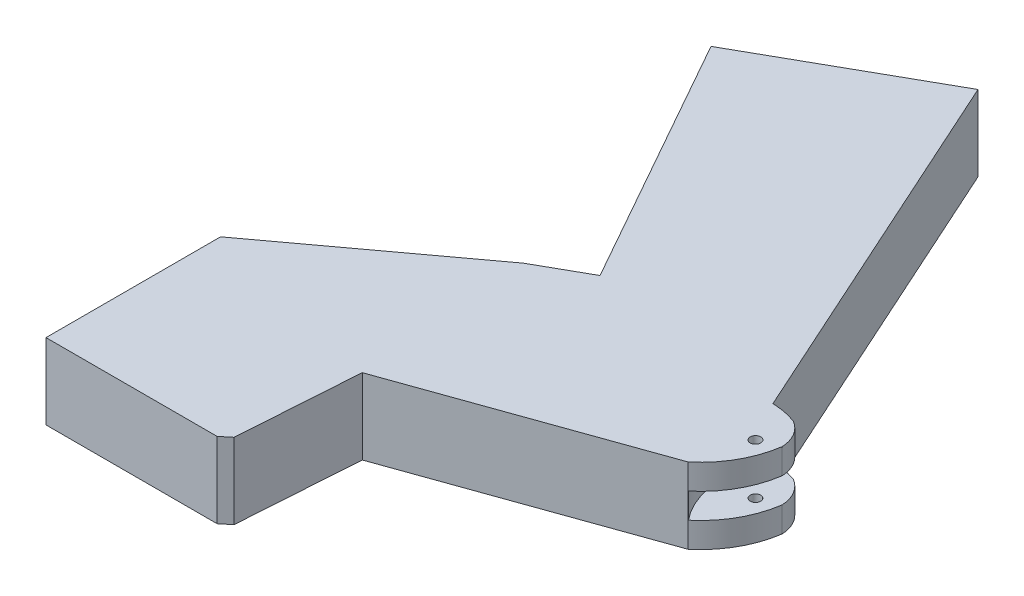
SolidWorks part; units mm, degrees
ref_plane "Front Plane" through (0, 0, 0) normal (0, 0, 1) x (1, 0, 0)
ref_plane "Top Plane" through (0, 0, 0) normal (0, 1, 0) x (1, 0, 0)
ref_plane "Right Plane" through (0, 0, 0) normal (1, 0, 0) x (0, 0, -1)
sketch "Sketch1" plane through (0, 0, 0) normal (0, 1, 0) x (1, 0, 0)
  line L0 (-30.4171, -25.1913) -> (-60.8342, -25.1913)
  line L1 (-8.2502, 1.4059) -> (-24.0712, 28.8087)
  line L2 (0, 0) -> (24.0712, 41.6926)
  line L4 (-24.0712, 28.8087) -> (-55.3265, 11.213)
  line L5 (-55.3265, 11.213) -> (-42.4527, -11.6547)
  line L6 (-42.4527, -11.6547) -> (-60.8342, -11.6547)
  line L7 (-60.8342, -11.6547) -> (-60.8342, -25.1913)
  line L9 (-9.9889, -8.2728) -> (-30.4171, -25.1913)
  arc A2 (-8.2502, 1.4059) -> (-9.9889, -8.2728) centre (-14.8493, -2.4041) cw
  point P3 (0, -25.1913)
  dimension "D2" = 7.62
  dimension "D1" = 60
  dimension "D3" = 54
extrude "Boss-Extrude1" add sketch "Sketch1" along normal blind 6 contours L9 L1 L4 L5 L6 L7 L0
sketch "Sketch2" plane through (0, 6, 0) normal (0, 1, 0) x (1, 0, 0)
  line L0 (-8.2502, 1.4059) -> (-24.0712, 28.8087) construction
  line L1 (-9.9889, -8.2728) -> (-30.4171, -25.1913) construction
  arc A0 (-6.2225, -2.1061) -> (-7.6083, -6.3012) centre (-5.7852, -4.577) ccw
sketch "Sketch3" plane through (0, 0, 0) normal (0.6378, 0, 0.7702) x (0.7702, 0, -0.6378)
  line L0 (-6.534, 6) -> (-6.534, 0) construction
  line L1 (-12.9427, 6) -> (-6.534, 6)
  line L2 (-12.9427, 6) -> (-12.9427, 4)
  line L3 (-12.9427, 4) -> (-6.534, 4)
  line L4 (-6.534, 6) -> (-6.534, 4)
  line L6 (-6.534, 0) -> (-12.9427, 0)
  line L7 (-6.534, 0) -> (-6.534, 2)
  line L8 (-6.534, 2) -> (-12.9427, 2)
  line L9 (-12.9427, 0) -> (-12.9427, 2)
  line L10 (-6.534, 4) -> (-12.9427, 4)
  line L11 (-6.534, 4) -> (-6.534, 2)
  line L12 (-6.534, 2) -> (-12.9427, 2)
  line L13 (-12.9427, 4) -> (-12.9427, 2)
  dimension "D1" = 2
  dimension "D2" = 2
  dimension "D3" = 2
revolve "Cut-Revolve1" cut sketch "Sketch3" angle 360 about L11
sketch "Sketch4" plane through (0, 6, 0) normal (0, 1, 0) x (1, 0, 0)
  circle A0 centre (-8.8256, -4.0865) radius 0.4182
extrude "Cut-Extrude1" cut sketch "Sketch4" against normal through all
sketch "Sketch5" plane through (0, 0, 0) normal (0, -1, 0) x (1, 0, 0)
  line L0 (-24.0712, -28.8087) -> (-10.6278, 0.899)
  line L1 (-24.0712, -28.8087) -> (-8.2502, -1.4059)
  arc A1 (-10.6278, 0.899) -> (-7.2401, 1.9995) centre (-10.836, 7.3043) ccw
  arc A3 (-7.2401, 1.9995) -> (-8.2502, -1.4059) centre (-14.8493, 2.4041) cw
extrude "Cut-Extrude2" cut sketch "Sketch5" against normal blind 7.0756
sketch "Sketch6" plane through (0, 0, 0) normal (0, -1, 0) x (-1, 0, 0)
  line L0 (8.6214, -1.2904) -> (6.2758, -0.7238)
  line L1 (6.2758, -0.7238) -> (7.3066, -3.4867)
  arc A0 (8.6214, -1.2904) -> (7.3066, -3.4867) centre (9.9836, -3.5976) ccw
extrude "Cut-Extrude3" cut sketch "Sketch6" against normal blind 7.0756
sketch "Sketch7" plane through (0, 6, 0) normal (0, 1, 0) x (1, 0, 0)
  line L0 (-9.9889, -8.2728) -> (-30.4171, -25.1913) construction
  line L1 (-9.9889, -8.2728) -> (-29.0389, -15.0581)
  line L2 (-29.0389, -15.0581) -> (-29.6827, -24.5831)
  line L3 (-29.6827, -24.5831) -> (-9.9889, -8.2728)
  dimension "D1" = 19.05
  dimension "D2" = 9.525
extrude "Cut-Extrude4" cut sketch "Sketch7" against normal blind 8.636
sketch "Sketch9" plane through (0, 6, 0) normal (0, 1, 0) x (1, 0, 0)
  line L0 (-30.4171, -25.1913) -> (-60.8342, -25.1913) construction
  line L1 (-60.8342, -11.6547) -> (-43.9887, -11.6547)
  line L2 (-60.8342, -11.6547) -> (-60.8342, -25.1913)
  line L3 (-60.8342, -25.1913) -> (-43.9887, -25.1913)
  line L4 (-43.9887, -11.6547) -> (-43.9887, -25.1913)
extrude "Cut-Extrude5" cut sketch "Sketch9" against normal blind 8.636
sketch "Sketch10" plane through (0, 0, 0) normal (0, -1, 0) x (1, 0, 0)
  line L0 (-43.9887, 11.6547) -> (-43.9887, 8.9264)
  line L1 (-55.3265, -11.213) -> (-42.4527, 11.6547) construction
  line L2 (-43.9887, 8.9264) -> (-42.4527, 11.6547)
  line L3 (-42.4527, 11.6547) -> (-43.9887, 11.6547)
extrude "Boss-Extrude2" add sketch "Sketch10" against normal up to surface (6 mm away) up to face at (-27.8976, 6, 7.2719)
sketch "Sketch11" plane through (0, 0, 0) normal (0, -1, 0) x (1, 0, 0)
  line L0 (-55.3265, -11.213) -> (-43.9887, 8.9264)
  line L1 (-43.9887, 8.9264) -> (-26.2818, -1.042)
  line L2 (-26.2818, -1.042) -> (-37.6197, -21.1814)
  line L3 (-37.6197, -21.1814) -> (-55.3265, -11.213)
  dimension "D1" = 20.32
extrude "Cut-Extrude6" cut sketch "Sketch11" against normal blind 21.59
sketch "Sketch12" plane through (0, 6, 0) normal (0, 1, 0) x (1, 0, 0)
  line L0 (24.8689, -11.3488) -> (-43.9887, -11.3488) construction
  line L1 (-43.9887, -25.1913) -> (-43.9887, -8.9264) construction
  line L2 (7.0434, -1.594) -> (-30.1682, -1.1459) construction
  line L3 (7.0722, -1.5417) -> (19.7376, 21.4421) construction
  line L4 (-43.9887, -8.9264) -> (-26.2818, 1.042) construction
  line L5 (-43.9887, -11.3488) -> (-30.1682, -1.1459)
  line L6 (-43.9887, -11.3488) -> (-43.9887, -8.9264)
  line L7 (-43.9887, -8.9264) -> (-30.1682, -1.1459)
extrude "Cut-Extrude7" cut sketch "Sketch12" against normal blind 20.574
